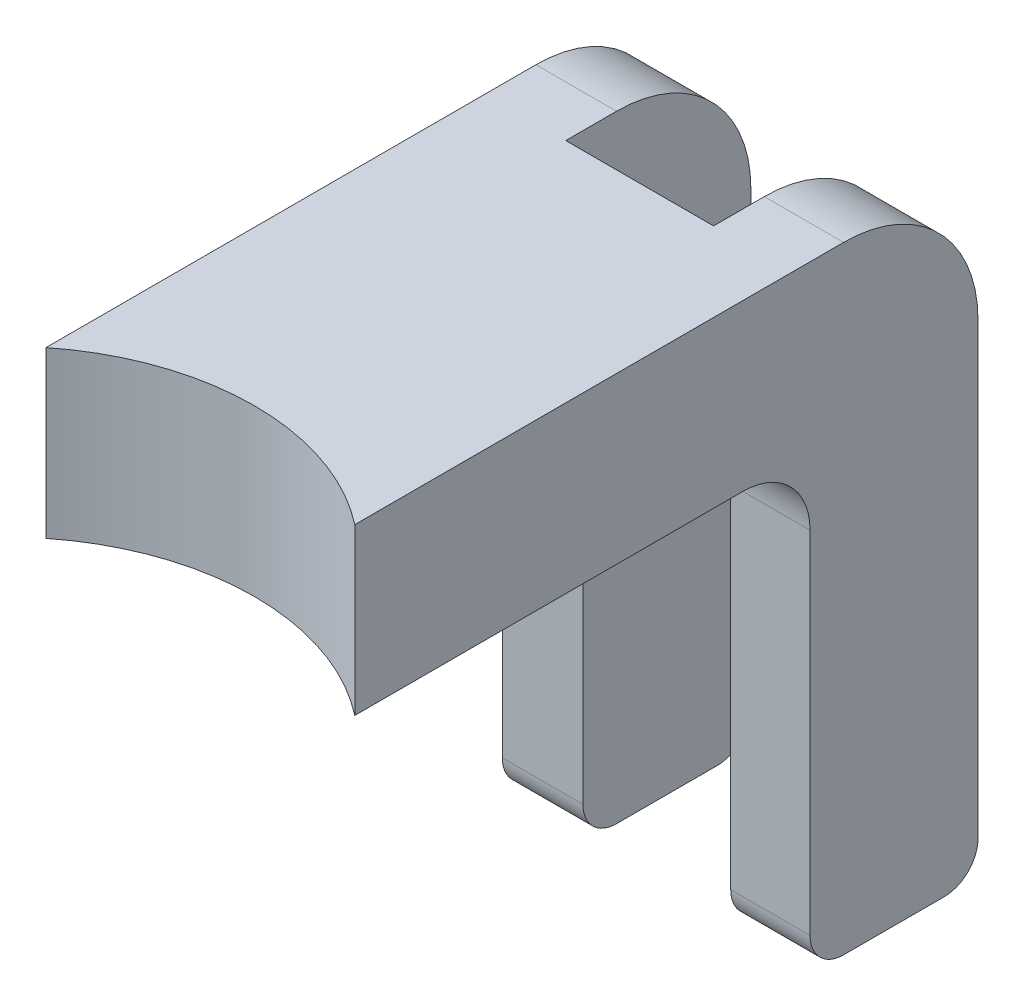
SolidWorks part; units mm, degrees
ref_plane "Спереди" through (0, 0, 0) normal (0, 0, 1) x (1, 0, 0)
ref_plane "Сверху" through (0, 0, 0) normal (0, 1, 0) x (1, 0, 0)
ref_plane "Справа" through (0, 0, 0) normal (1, 0, 0) x (0, 0, -1)
sketch "Эскиз1" plane through (0, 0, 0) normal (1, 0, 0) x (0, 0, -1)
  line L0 (3.6837, 0) -> (3.6837, -24.5969)
  line L1 (3.6837, -24.5969) -> (49.1322, -24.5969)
  line L3 (3.6837, 0) -> (64.1322, 0)
  line L7 (59.1322, -34.5969) -> (59.1322, -86.8316)
  line L8 (64.1322, -91.8316) -> (79.1322, -91.8316)
  line L9 (84.1322, -86.8316) -> (84.1322, -20)
  arc A0 (84.1322, -20) -> (64.1322, 0) centre (64.1322, -20) ccw
  arc A1 (59.1322, -34.5969) -> (49.1322, -24.5969) centre (49.1322, -34.5969) ccw
  arc A2 (64.1322, -91.8316) -> (59.1322, -86.8316) centre (64.1322, -86.8316) cw
  arc A3 (84.1322, -86.8316) -> (79.1322, -91.8316) centre (79.1322, -86.8316) cw
  dimension "D1" = 20
  dimension "D2" = 10
  dimension "D3" = 5
  dimension "D4" = 91.8316
extrude "Вытянуть1" add sketch "Эскиз1" along normal blind 46 from offset 3
sketch "Эскиз2" plane through (0, 0, 0) normal (0, 1, 0) x (1, 0, 0)
  line L0 (20, 84.1322) -> (20, 104.5676) construction
  line L1 (9, 97.5814) -> (9, 56.5775)
  line L3 (31, 97.5814) -> (31, 56.5775)
  line L5 (9, 97.5814) -> (31, 97.5814)
  line L6 (31, 56.5775) -> (9, 56.5775)
  circle A0 centre (20, 18.9317) radius 15 construction
  dimension "D1" = 30
  dimension "D2" = 11
extrude "Вытянуть2" cut sketch "Эскиз2" against normal mid plane 230
sketch "Эскиз3" plane through (0, 0, 0) normal (1, 0, 0) x (0, 0, -1)
  line L0 (5.675, 15.3538) -> (5.675, 28.3206) construction
  line L3 (31.675, 29.692) -> (31.675, 13.6083) construction
  line L6 (18.675, 32.1857) -> (18.675, 12.9849) construction
  circle A0 centre (71.6322, -58) radius 4
  circle A1 centre (18.675, -12.6282) radius 2.5
  dimension "D2" = 13
extrude "Вырез-Вытянуть1" [suppressed] cut sketch "Эскиз3" against normal mid plane 110
sketch "Эскиз4" plane through (0, 0, -3.6837) normal (0, 0, 1) x (1, 0, 0)
  line L0 (57.0034, -24.5969) -> (-16.9966, -24.5969)
  line L1 (57.0034, -24.5969) -> (57.0034, 0)
  line L2 (57.0034, 0) -> (-16.9966, 0)
  line L3 (-16.9966, 0) -> (-16.9966, -24.5969)
  line L4 (47.0034, -21.4606) -> (47.0034, -1.4606) construction
  line L6 (-6.9966, -1.4606) -> (-6.9966, -21.4606) construction
  dimension "D1" = 10
  dimension "D2" = 10
extrude "Вытянуть3" add sketch "Эскиз4" along normal blind 55
sketch "Эскиз6" plane through (0, 0, 0) normal (0, 1, 0) x (1, 0, 0)
  line L0 (47.0034, -53.7136) -> (47.0034, -12.467)
  line L2 (-6.9966, -12.467) -> (-6.9966, -53.7136)
  line L3 (-6.9966, -53.7136) -> (47.0034, -53.7136)
  arc A0 (47.0034, -12.467) -> (-6.9966, -12.467) centre (20.0034, -37.7653) ccw
extrude "Вырез-Вытянуть2" cut sketch "Эскиз6" along normal mid plane 100
fillet "Скругление2" radius 4 2 edges at (57.0034, -12.2984, -3.6837) (-16.9966, -12.2984, -3.6837)
sketch "Эскиз7" plane through (57.0034, 0, 0) normal (1, 0, 0) x (0, 0, -1)
  circle A0 centre (-35.6235, -11.4606) radius 3
extrude "Вырез-Вытянуть3" cut sketch "Эскиз7" against normal mid plane 180
fillet "Скругление3" radius 10 2 edges
sketch "Эскиз8" plane through (0, 0, 0) normal (0, 0, 1) x (1, 0, 0)
  line L0 (-16.9966, 0) -> (57.0034, -72.4866) construction
  line L1 (-16.9966, 0) -> (57.0034, 0) construction
  line L2 (-16.9966, 0) -> (-16.9966, -72.4866) construction
  line L3 (-16.9966, -72.4866) -> (57.0034, -72.4866) construction
  line L4 (57.0034, 0) -> (57.0034, -72.4866) construction
  line L5 (57.0034, 0) -> (-16.9966, -72.4866) construction
  circle A0 centre (20.0034, -36.2433) radius 50
sketch "Эскиз9" plane through (57.0034, 0, 0) normal (1, 0, 0) x (0, 0, -1)
  line L1 (-54.1934, 6.261) -> (111.0711, 6.261)
  line L2 (-54.1934, 6.261) -> (-54.1934, -113.7179)
  line L3 (-54.1934, -113.7179) -> (111.0711, -113.7179)
  line L4 (111.0711, 6.261) -> (111.0711, -113.7179)
extrude "Вытянуть5" cut sketch "Эскиз9" against normal blind 14.2
sketch "Эскиз10" plane through (-16.9966, 0, 0) normal (-1, 0, 0) x (0, 0, 1)
  line L1 (-109.5585, 17.0443) -> (60.0222, 17.0443)
  line L2 (-109.5585, 17.0443) -> (-109.5585, -98.1008)
  line L3 (-109.5585, -98.1008) -> (60.0222, -98.1008)
  line L4 (60.0222, 17.0443) -> (60.0222, -98.1008)
extrude "Вытянуть6" cut sketch "Эскиз10" against normal blind 14
